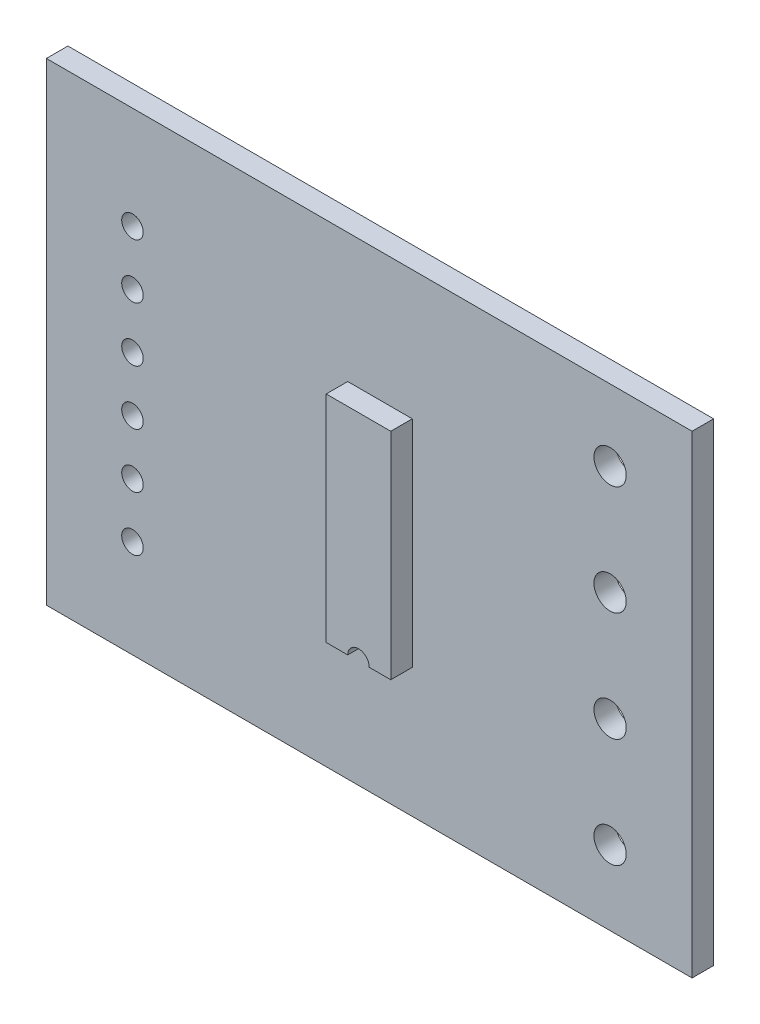
SolidWorks part; units mm, degrees
ref_plane "正面" through (0, 0, 0) normal (0, 0, 1) x (1, 0, 0)
ref_plane "平面" through (0, 0, 0) normal (0, 1, 0) x (1, 0, 0)
ref_plane "右側面" through (0, 0, 0) normal (1, 0, 0) x (0, 0, -1)
sketch "ｽｹｯﾁ1" plane through (0, 0, 0) normal (0, 0, 1) x (1, 0, 0)
  line L1 (0, 0) -> (30, 0)
  line L2 (0, 0) -> (0, 22)
  line L3 (0, 22) -> (30, 22)
  line L4 (30, 0) -> (30, 22)
  dimension "D1" = 22
  dimension "D2" = 30
extrude "ﾎﾞｽ - 押し出し1" add sketch "ｽｹｯﾁ1" along normal blind 1
sketch "ｽｹｯﾁ2" plane through (0, 0, 1) normal (0, 0, 1) x (1, 0, 0)
  line L0 (4, 17.25) -> (4, 4.55) construction
  line L1 (30, 22) -> (0, 22) construction
  line L2 (0, 22) -> (0, 0) construction
  line L3 (26.19, 18.69) -> (26.19, 13.61) construction
  line L4 (30, 0) -> (30, 22) construction
  line L5 (26.19, 8.53) -> (26.19, 3.45) construction
  circle A0 centre (4, 17.25) radius 0.5
  circle A1 centre (4, 14.71) radius 0.5
  circle A2 centre (4, 12.17) radius 0.5
  circle A3 centre (4, 9.63) radius 0.5
  circle A4 centre (4, 7.09) radius 0.5
  circle A5 centre (4, 4.55) radius 0.5
  circle A6 centre (26.19, 18.69) radius 0.75
  circle A7 centre (26.19, 13.61) radius 0.75
  circle A8 centre (26.19, 8.53) radius 0.75
  circle A9 centre (26.19, 3.45) radius 0.75
  dimension "D3" = 1
  dimension "D9" = 1.5
  dimension "D10" = 1.5
  dimension "D13" = 1.5
  dimension "D14" = 1.5
  dimension "D1" = 4.75
  dimension "D2" = 4
  dimension "D5" = 12.7
  dimension "D6" = 3.81
  dimension "D7" = 3.31
  dimension "D8" = 5.08
  dimension "D11" = 5.08
  dimension "D12" = 13.47
  dimension "D4" = 6
extrude "ｶｯﾄ - 押し出し1" cut sketch "ｽｹｯﾁ2" against normal through all
sketch "ｽｹｯﾁ3" plane through (0, 0, 1) normal (0, 0, 1) x (1, 0, 0)
  line L0 (0, 22) -> (0, 0) construction
  line L1 (14, 16) -> (17, 16)
  line L2 (14, 16) -> (14, 6)
  line L3 (14, 6) -> (17, 6)
  line L4 (17, 16) -> (17, 6)
  line L5 (30, 22) -> (0, 22) construction
  dimension "D1" = 3
  dimension "D2" = 10
  dimension "D3" = 14
  dimension "D4" = 6
extrude "ﾎﾞｽ - 押し出し2" add sketch "ｽｹｯﾁ3" along normal blind 1
sketch "ｽｹｯﾁ4" plane through (0, 0, 2) normal (0, 0, 1) x (1, 0, 0)
  line L0 (14, 6) -> (17, 6) construction
  circle A0 centre (15.5, 6) radius 0.5
  dimension "D1" = 1
extrude "ｶｯﾄ - 押し出し2" cut sketch "ｽｹｯﾁ4" against normal blind 1
